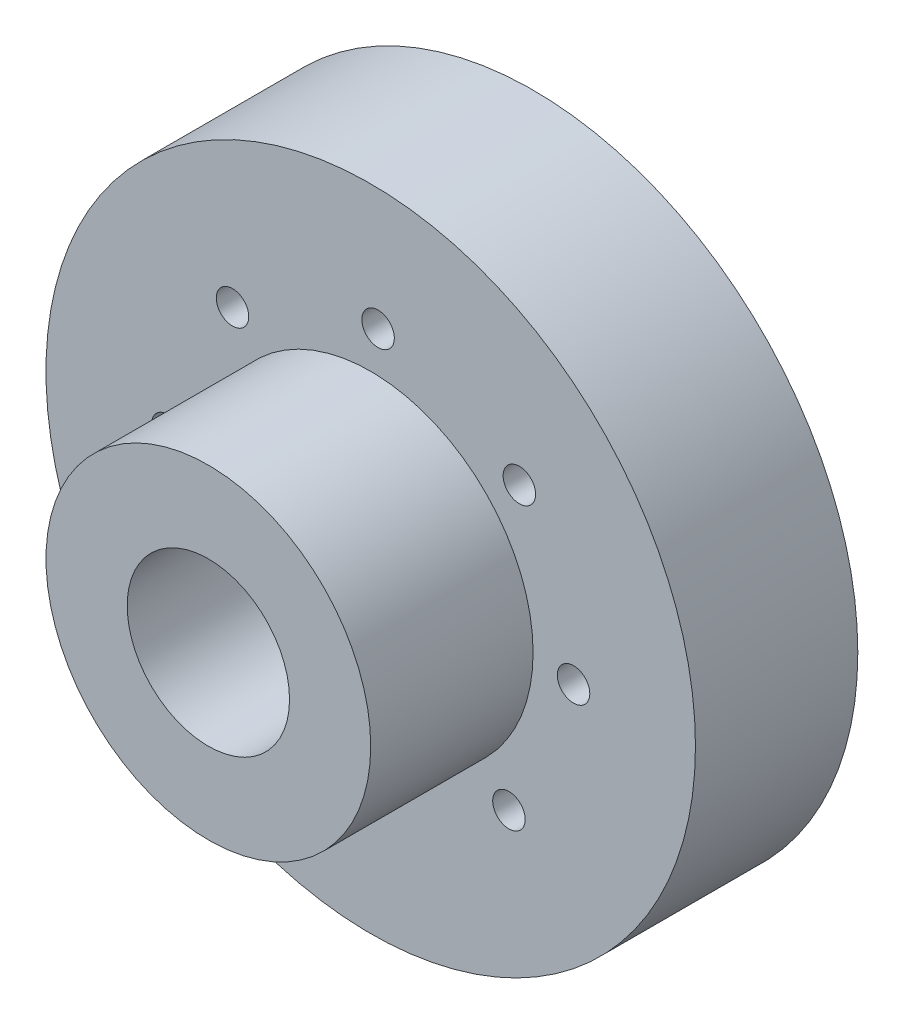
SolidWorks part; units mm, degrees
material "7075-O (SS)"
ref_plane "Front Plane" through (0, 0, 0) normal (0, 0, 1) x (1, 0, 0)
ref_plane "Top Plane" through (0, 0, 0) normal (0, 1, 0) x (1, 0, 0)
ref_plane "Right Plane" through (0, 0, 0) normal (1, 0, 0) x (0, 0, -1)
sketch "Sketch1" plane through (0, 0, 0) normal (0, 0, 1) x (1, 0, 0)
  circle A0 centre (0, 0) radius 12.7
  dimension "D1" = 25.4
extrude "Boss-Extrude1" add sketch "Sketch1" along normal blind 12.7
sketch "Sketch2" plane through (0, 0, 12.7) normal (0, 0, 1) x (1, 0, 0)
  circle A0 centre (0, 0) radius 3.175
  dimension "D1" = 6.35
extrude "Cut-Extrude1" cut sketch "Sketch2" against normal through all
sketch "Sketch3" plane through (0, 0, 12.7) normal (0, 0, 1) x (1, 0, 0)
  circle A0 centre (0, 0) radius 6.35
  circle A1 centre (0, 0) radius 15.4936
  dimension "D1" = 12.7
extrude "Cut-Extrude2" cut sketch "Sketch3" against normal blind 6.35
sketch "Sketch4" plane through (0, 0, 6.35) normal (0, 0, 1) x (1, 0, 0)
  circle A0 centre (0, 0) radius 7.9375 construction
  circle A1 centre (0.2881, 7.9323) radius 0.635
  circle A2 centre (5.8127, 5.4052) radius 0.635
  circle A3 centre (7.9323, -0.2881) radius 0.635
  circle A4 centre (5.4052, -5.8127) radius 0.635
  circle A5 centre (-0.2881, -7.9323) radius 0.635
  circle A6 centre (-5.8127, -5.4052) radius 0.635
  circle A7 centre (-7.9323, 0.2881) radius 0.635
  circle A8 centre (-5.4052, 5.8127) radius 0.635
  dimension "D1" = 15.875
  dimension "D2" = 1.27
  dimension "D3" = 8
extrude "Cut-Extrude3" cut sketch "Sketch4" against normal through all
